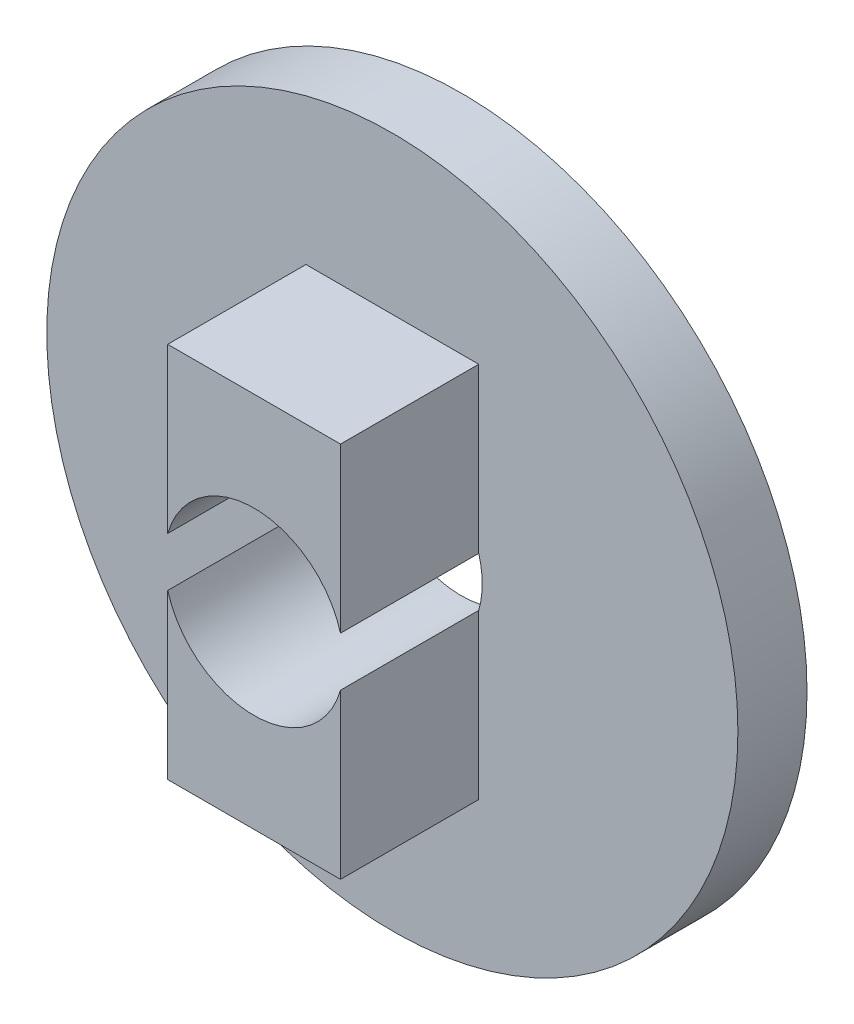
SolidWorks part; units mm, degrees
material "6061 Alloy"
ref_plane "Front Plane" through (0, 0, 0) normal (0, 0, 1) x (1, 0, 0)
ref_plane "Top Plane" through (0, 0, 0) normal (0, 1, 0) x (1, 0, 0)
ref_plane "Right Plane" through (0, 0, 0) normal (1, 0, 0) x (0, 0, -1)
ref_plane "Plane1" through (0, 0, 0) normal (0, -1, 0) x (1, 0, 0)
sketch "Sketch1" plane through (0, 0, 0) normal (0, 0, 1) x (1, 0, 0)
  circle A0 centre (0, 0) radius 5
extrude "Boss-Extrude1" add sketch "Sketch1" along normal blind 1
sketch "Sketch2" plane through (0, 0, 1) normal (0, 0, 1) x (1, 0, 0)
  line L1 (-1.25, -2.7272) -> (1.25, -2.7272)
  line L2 (-1.25, -2.7272) -> (-1.25, 2.7272)
  line L3 (-1.25, 2.7272) -> (1.25, 2.7272)
  line L4 (1.25, -2.7272) -> (1.25, 2.7272)
  line L5 (-1.25, -2.7272) -> (1.25, 2.7272) construction
  line L6 (-1.25, 2.7272) -> (1.25, -2.7272) construction
  circle A3 centre (0, 0) radius 3 construction
  dimension "D2" = 6
  dimension "D1" = 2.5
extrude "Boss-Extrude2" add sketch "Sketch2" along normal blind 2 contours L1 L4 L3 L2
sketch "Sketch9" plane through (0, 0, 3) normal (0, 0, 1) x (1, 0, 0)
  point P0 (0, 0)
hole_wizard "Ø2.6 (2.6) Diameter Hole1" positions "3DSketch4" profile "Sketch10" hole size "Ø2.6" standard "ANSI Metric"
sketch3d "3DSketch4"
  point P0 (0, 0, 3)
sketch "Sketch10" plane through (0, 0, 3) normal (1, 0, 0) x (0, -1, 0)
  line L0 (0, 0) -> (0, 9.7811)
  line L1 (0, 9.7811) -> (1.3, 9)
  line L2 (1.3, 9) -> (1.3, 0)
  line L5 (1.3, 0) -> (0, 0)
  line L10 (0, 9.7811) -> (-1.3, 9) construction
  line L11 (0, -6.35) -> (0, 107.95) construction
  dimension "Hole Dia." = 2.6
  dimension "Hole Depth" = 9
  dimension "Drill Angle" = 118
